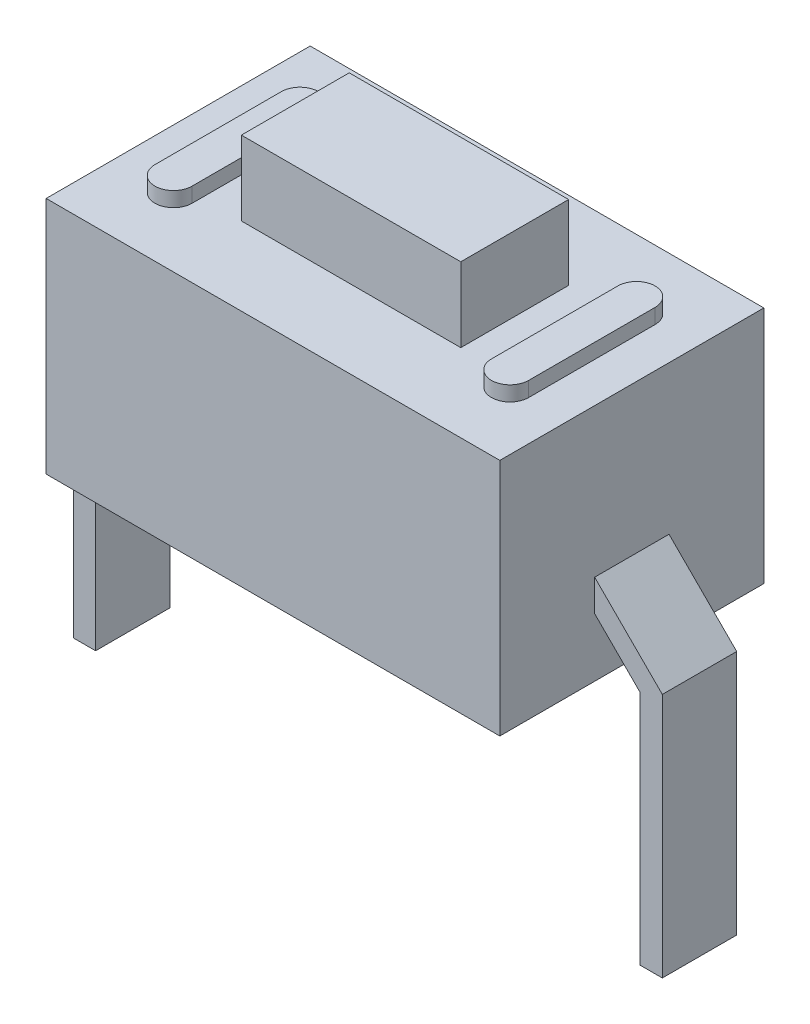
SolidWorks part; units mm, degrees
ref_plane "Front Plane" through (0, 0, 0) normal (0, 0, 1) x (1, 0, 0)
ref_plane "Top Plane" through (0, 0, 0) normal (0, 1, 0) x (1, 0, 0)
ref_plane "Right Plane" through (0, 0, 0) normal (1, 0, 0) x (0, 0, -1)
sketch "Sketch1" plane through (0, 0, 0) normal (0, 1, 0) x (1, 0, 0)
  line L1 (-3.05, 1.775) -> (3.05, 1.775)
  line L2 (-3.05, 1.775) -> (-3.05, -1.775)
  line L3 (-3.05, -1.775) -> (3.05, -1.775)
  line L4 (3.05, 1.775) -> (3.05, -1.775)
  line L5 (-3.05, 1.775) -> (3.05, -1.775) construction
  line L6 (-3.05, -1.775) -> (3.05, 1.775) construction
  point P0 (0, 0)
  dimension "D1" = 6.1
  dimension "D2" = 3.55
extrude "Boss-Extrude1" add sketch "Sketch1" along normal blind 3.21
sketch "Sketch2" plane through (0, 3.21, 0) normal (0, 1, 0) x (1, 0, 0)
  line L1 (-1.475, 0.725) -> (1.475, 0.725)
  line L2 (-1.475, 0.725) -> (-1.475, -0.725)
  line L3 (-1.475, -0.725) -> (1.475, -0.725)
  line L4 (1.475, 0.725) -> (1.475, -0.725)
  line L5 (-1.475, 0.725) -> (1.475, -0.725) construction
  line L6 (-1.475, -0.725) -> (1.475, 0.725) construction
  point P0 (0, 0)
  dimension "D1" = 1.45
  dimension "D2" = 2.95
extrude "Boss-Extrude2" add sketch "Sketch2" along normal blind 1
sketch "Sketch3" plane through (0, 3.21, 0) normal (0, 1, 0) x (1, 0, 0)
  line L0 (0, 0) -> (0, 1.775) construction
  line L1 (3.05, 1.775) -> (-3.05, 1.775) construction
  line L2 (0, 0) -> (-3.05, 0) construction
  line L3 (-3.05, 1.775) -> (-3.05, -1.775) construction
  line L4 (-2.2625, 0.85) -> (-2.2625, -0.85) construction
  line L5 (-2.0125, 0.85) -> (-2.0125, -0.85)
  line L6 (-2.5125, 0.85) -> (-2.5125, -0.85)
  line L7 (-2.5125, -0.85) -> (-3.05, -0.85) construction
  line L8 (-2.0125, -0.725) -> (-1.475, -0.725) construction
  line L9 (2.2625, 0.85) -> (2.2625, -0.85) construction
  line L10 (2.0125, 0.85) -> (2.0125, -0.85)
  line L11 (2.5125, 0.85) -> (2.5125, -0.85)
  arc A0 (-2.0125, 0.85) -> (-2.5125, 0.85) centre (-2.2625, 0.85) ccw
  arc A1 (-2.5125, -0.85) -> (-2.0125, -0.85) centre (-2.2625, -0.85) ccw
  arc A2 (2.0125, 0.85) -> (2.5125, 0.85) centre (2.2625, 0.85) cw
  arc A3 (2.5125, -0.85) -> (2.0125, -0.85) centre (2.2625, -0.85) cw
  point P10 (-2.2625, 0)
  point P22 (2.2625, 0)
  dimension "D2" = 0.25
  dimension "D1" = 1.7
extrude "Boss-Extrude3" add sketch "Sketch3" along normal blind 0.2
sketch "Sketch4" plane through (0, 0, 0) normal (0, 0, 1) x (1, 0, 0)
  line L0 (0, 0) -> (0, -3) construction
  line L1 (-3.05, 0) -> (3.05, 0) construction
  line L2 (-3.81, -3) -> (3.81, -3) construction
  line L3 (-2.5475, 1.5025) -> (-3.81, 0.24)
  line L4 (-3.05, 3.21) -> (-3.05, 0) construction
  line L5 (-3.81, 0.24) -> (-3.81, -3)
  line L6 (2.5475, 1.5025) -> (3.81, 0.24)
  line L7 (3.81, 0.24) -> (3.81, -3)
  point P7 (0, -3)
  point P14 (-2.5475, 1.5025)
  point P16 (-3.05, 1)
  dimension "D1" = 3
  dimension "D2" = 7.62
  dimension "D3" = 45
  dimension "D4" = 1
extrude "Extrude-Thin1" add sketch "Sketch4" along normal mid plane 1 thin thin type mid plane wall 0.3
